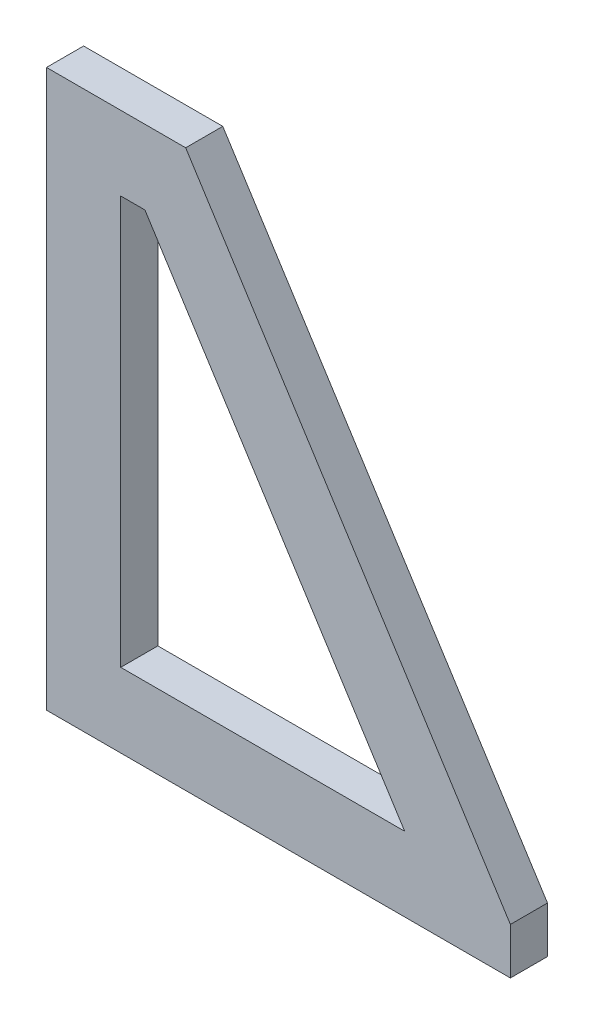
SolidWorks part; units mm, degrees
material "1060 合金"
ref_plane "前视基准面" through (0, 0, 0) normal (0, 0, 1) x (1, 0, 0)
ref_plane "上视基准面" through (0, 0, 0) normal (0, 1, 0) x (1, 0, 0)
ref_plane "右视基准面" through (0, 0, 0) normal (1, 0, 0) x (0, 0, -1)
sketch "草图1" plane through (0, 0, 0) normal (0, 0, 1) x (1, 0, 0)
  line L0 (0, 0) -> (100, 0)
  line L1 (0, 120) -> (30, 120)
  line L2 (0, 120) -> (0, 0)
  line L3 (30, 120) -> (100, 10)
  line L4 (100, 10) -> (100, 0)
  line L5 (16, 104) -> (21.2169, 104)
  line L6 (21.2169, 104) -> (77.2169, 16)
  line L7 (77.2169, 16) -> (77.2169, 16)
  line L8 (16, 16) -> (77.2169, 16)
  line L9 (16, 104) -> (16, 16)
  dimension "D1" = 100
  dimension "D2" = 120
  dimension "D3" = 30
  dimension "D4" = 10
  dimension "D5" = 16
extrude "凸台-拉伸1" add sketch "草图1" along normal mid plane 8
